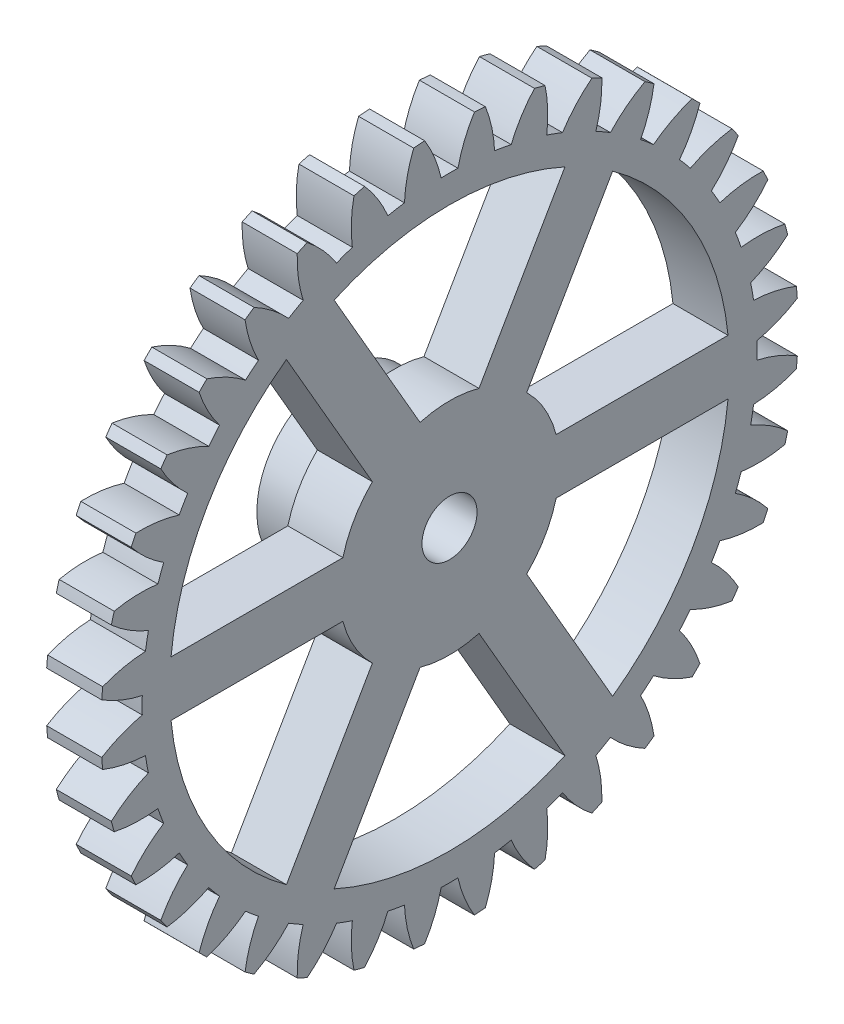
SolidWorks part; units mm, degrees
ref_plane "Plane1" through (0, 0, 0) normal (0, 0, 1) x (1, 0, 0)
ref_plane "Plane2" through (0, 0, 0) normal (0, 1, 0) x (1, 0, 0)
ref_plane "Plane3" through (0, 0, 0) normal (1, 0, 0) x (0, 0, -1)
sketch "HoldingSke" plane through (0, 0, 0) normal (0, 1, 0) x (1, 0, 0)
  line L0 (0, 0) -> (246.5884, -179.1569)
  line L1 (-15, 0) -> (100, 0) construction
  line L2 (0, 0) -> (-2.1039, 2.3779)
  line L3 (0, 0) -> (-11.863, 4.5341)
  line L4 (0, 0) -> (6.9867, 5.0761)
  line L5 (0, 0) -> (-11.8993, -4.4381)
  line L6 (0, 0) -> (-5.2639, -3.5516)
  line L7 (-2.1039, 2.3779) -> (0.6298, 14.7802)
  line L8 (-76.2, 54.61) -> (-69.596, 54.61)
  line L9 (-71.009, 38.7566) -> (-53.1078, 45.2721)
  line L10 (-76.2, 71.12) -> (104.1128, 71.12)
  line L11 (0, 0) -> (-6.35, 0)
  line L12 (-76.2, 101.6) -> (-76.1147, 101.6)
  line L13 (24.9733, 27.94) -> (52.9518, 28.4284)
  line L14 (24.9733, 27.94) -> (24.9746, 27.94)
  line L15 (24.9733, 27.94) -> (100.4006, 29.5858)
  circle A0 centre (0, 0) radius 3.175
  circle A1 centre (0, 0) radius 9.525
  circle A2 centre (0, 0) radius 9.525
  circle A3 centre (0, 0) radius 3.175
  dimension "MHD" = 19.05
  dimension "Hub_dia" = 19.05
  dimension "Bore" = 6.35
  dimension "MBD" = 6.35
  dimension "Num_teeth" = 36
  dimension "Pitch" = 304.8
  dimension "Overall_len" = 12.7
  dimension "Show_teeth" = 36
  dimension "Thickness" = 6.35
  dimension "OAL" = 12.7001
  dimension "T_dim" = 6.604
  dimension "Ap" = 20
  dimension "H" = 19.05
  dimension "Pitch_radius" = 180.3128
  dimension "Width" = 6.35
  dimension "Backlash" = 0.0853
  dimension "Addendum_fac" = 1
  dimension "Dedendum_fac" = 1.25
  dimension "Clearance_fac" = 0.25
  dimension "Dedendum_add" = 0.0013
sketch "BasProSke" plane through (0, 0, 0) normal (0, 1, 0) x (1, 0, 0)
  line L0 (-10, 0) -> (60, 0) construction
  line L1 (0, 0) -> (0, 40.2167)
  line L2 (0, 0) -> (6.35, 0)
  line L3 (6.35, 0) -> (6.35, 40.2167)
  line L4 (6.35, 40.2167) -> (0, 40.2167)
  dimension "Thickness" = 6.35
  dimension "Diameter" = 80.4333
revolve "Base-Revolve" add sketch "BasProSke" angle 360 about L0
sketch "TooCutSke" plane through (0, 0, 0) normal (1, 0, 0) x (0, 0, -1)
  line L1 (0, 0) -> (0, 107) construction
  line L2 (0, 0) -> (-1.8112, 38.0569) construction
  line L3 (0, 0) -> (-6.636, 75.8502) construction
  line L4 (-1.8112, 38.0569) -> (-3.318, 37.9251) construction
  arc A0 (0.9706, 35.4396) -> (-0.9706, 35.4396) centre (0, 0) ccw
  arc A1 (2.8897, 40.1382) -> (-2.8897, 40.1382) centre (0, 0) ccw
  circle A2 centre (0, 0) radius 38.1 construction
  circle A3 centre (0, 0) radius 35.8023 construction
  arc A4 (-0.9706, 35.4396) -> (-2.8897, 40.1382) centre (-15.8417, 32.1068) ccw
  arc A5 (2.8897, 40.1382) -> (0.9706, 35.4396) centre (15.8417, 32.1068) ccw
  dimension "Root_dia" = 70.9058
  dimension "Overcut_dia" = 80.4841
  dimension "Pitch_dia" = 76.2
  dimension "Base_dia" = 71.6046
  dimension "Flank_rad" = 15.24
  dimension "Half_ang" = 5
  dimension "Half_CT" = 1.5125
extrude "ToothCut" cut sketch "TooCutSke" along normal through all
fillet "Breaks" [suppressed] radius 0.0423
fillet "RootFillets" [suppressed] radius 0.5304
pattern_circular "TeethCuts" count 36 every 10 about axis through (-10, 0, 0) along (1, 0, 0) of "ToothCut", "RootFillets", "Breaks"
sketch "HubNeaOneSke" plane through (0, 0, 0) normal (-1, 0, 0) x (0, 0, 1)
  circle A0 centre (0, 0) radius 9.525
  dimension "Diameter" = 19.05
extrude "HubNearOne" add sketch "HubNeaOneSke" along normal blind 6.3501
sketch "HubNeaBotSke" plane through (0, 0, 0) normal (-1, 0, 0) x (0, 0, 1)
  circle A0 centre (0, 0) radius 9.525
  dimension "Diameter" = 19.05
extrude "HubNearBoth" [suppressed] add sketch "HubNeaBotSke" along normal blind 3.175
ref_plane "FarPln" through (6.35, 0, 0) normal (1, 0, 0) x (0, 0, -1)
sketch "HubFarSke" plane through (6.35, 0, 0) normal (1, 0, 0) x (0, 0, -1)
  circle A0 centre (0, 0) radius 9.525
  dimension "Diameter" = 19.05
extrude "HubFar" [suppressed] add sketch "HubFarSke" along normal blind 3.175
sketch "BorSke" plane through (0, 0, 0) normal (1, 0, 0) x (0, 0, -1)
  circle A0 centre (0, 0) radius 3.175
  dimension "Diameter" = 6.35
extrude "Bore" cut sketch "BorSke" along normal mid plane 25.4001
sketch "KeySke" plane through (0, 0, 0) normal (1, 0, 0) x (0, 0, -1)
  line L0 (-0.127, 0) -> (-0.127, 3.429)
  line L1 (-0.127, 3.429) -> (0.127, 3.429)
  line L2 (0.127, 3.429) -> (0.127, 0)
  line L3 (0, 0) -> (0, 34) construction
  line L4 (-0.127, 0) -> (0.127, 0)
  dimension "Offset" = 3.429
  dimension "Width" = 0.254
extrude "Keyway" [suppressed] cut sketch "KeySke" along normal mid plane 25.4001
pattern_circular "Keyway2" [suppressed] count 2 every 90 about axis through (-10, 0, 0) along (1, 0, 0)
sketch "Sketch1" plane through (0, 0, 0) normal (-1, 0, 0) x (0, 0, 1)
  line L0 (-9.525, 0) -> (-35.4529, 0) construction
  line L1 (-4.7625, 8.2489) -> (-17.7264, 30.7031) construction
  line L2 (0, 0) -> (-9.525, 0) construction
  line L3 (0, 0) -> (-4.7625, 8.2489) construction
  line L4 (-8.898, 9.0618) -> (-18.8103, 26.2304)
  line L5 (-12.2967, 3.175) -> (-32.1214, 3.175)
  arc A0 (-35.4396, 0.9706) -> (-35.4396, -0.9706) centre (0, 0) ccw construction
  arc A1 (-35.4529, 0) -> (-17.7264, 30.7031) centre (0, 0) cw construction
  arc A2 (-9.525, 0) -> (-4.7625, 8.2489) centre (0, 0) cw construction
  circle A3 centre (0, 0) radius 9.525 construction
  arc A4 (-32.1214, 3.175) -> (-18.8103, 26.2304) centre (0, 0) cw
  arc A5 (-12.2967, 3.175) -> (-8.898, 9.0618) centre (0, 0) cw
  dimension "D1" = 60
  dimension "D2" = 3.175
extrude "Cut-Extrude1" cut sketch "Sketch1" against normal through all
pattern_circular "CirPattern1" count 6 over 360 about axis through (0, 0, 0) along (1, 0, 0) of "Cut-Extrude1"
equation "' \"Pitch@HoldingSke\" = 4"
equation "' \"Num_teeth@HoldingSke\" = 12"
equation "' \"Ap@HoldingSke\" =  20"
equation "' \"Ap@HoldingSke\" = 20"
equation "' \"Width@HoldingSke\" = 0.5"
equation "' \"Hub_dia@HoldingSke\"= 1"
equation "' \"Hub_dia@HoldingSke\" = 1"
equation "' \"Overall_len@HoldingSke\" = 1.0"
equation "' \"Bore@HoldingSke\" = 0.75"
equation "' \"T_dim@HoldingSke\" = 0.85"
equation "' \"Width@KeySke\" = 0.25"
equation "' \"Show_teeth@HoldingSke\" = 13"
equation "' \"Backlash@HoldingSke\" = 0.009"
equation "' \"Addendum_fac@HoldingSke\" = 1.0"
equation "' \"Dedendum_fac@HoldingSke\" = 1.25"
equation "' \"Dedendum_add@HoldingSke\" = 0.00005"
equation "' \"Clearance_fac@HoldingSke\" = 0.25"
equation "' \"Pitch@HoldingSke\" = 0.5"
equation "' \"Num_teeth@HoldingSke\" = 23"
equation "' \"Show_teeth@HoldingSke\" = 23"
equation "' \"Backlash@HoldingSke\" = 0.0375"
equation "\"Overcut_dia@TooCutSke\" = (\"Num_teeth@HoldingSke\" + 2 * \"Addendum_fac@HoldingSke\") / \"Pitch@HoldingSke\" + 0.002"
equation "\"Pitch_dia@TooCutSke\" = \"Num_teeth@HoldingSke\" / \"Pitch@HoldingSke\""
equation "\"Base_dia@TooCutSke\" = \"Num_teeth@HoldingSke\" / \"Pitch@HoldingSke\" * cos((\"Ap@HoldingSke\"  * 3.14159265 / 180))"
equation "\"Root_dia@TooCutSke\" = (\"Num_teeth@HoldingSke\" + 2) / \"Pitch@HoldingSke\" - 2 * (\"Addendum_fac@HoldingSke\" + \"Dedendum_fac@HoldingSke\") / \"Pitch@HoldingSke\" - \"Dedendum_add@HoldingSke\" * 2"
equation "\"Half_ang@TooCutSke\" = 180 / \"Num_teeth@HoldingSke\""
equation "\"Half_CT@TooCutSke\" = \"Num_teeth@HoldingSke\" / \"Pitch@HoldingSke\" * sin((3.14159265 / 2 / \"Num_teeth@HoldingSke\")) / 2 - 7 * \"Backlash@HoldingSke\" / 4"
equation "\"Flank_rad@TooCutSke\" = \"Num_teeth@HoldingSke\" / \"Pitch@HoldingSke\" / 5"
equation "\"Radius@RootFillets\" = \"Clearance_fac@HoldingSke\" / \"Pitch@HoldingSke\" + \"Dedendum_add@HoldingSke\""
equation "\"Break_rad@Breaks\" = 0.02 / \"Pitch@HoldingSke\""
equation "\"Thickness@HoldingSke\" = \"Width@HoldingSke\""
equation "\"OAL@HoldingSke\" = \"Thickness@HoldingSke\""
equation "\"MHD@HoldingSke\" = (\"Num_teeth@HoldingSke\" + 2) / \"Pitch@HoldingSke\" - 2 * (\"Addendum_fac@HoldingSke\" + \"Dedendum_fac@HoldingSke\")  / \"Pitch@HoldingSke\" - \"Dedendum_add@HoldingSke\" * 2"
equation "\"MBD@HoldingSke\" = (\"Num_teeth@HoldingSke\" + 2) / \"Pitch@HoldingSke\" - 2 * (\"Addendum_fac@HoldingSke\" + \"Dedendum_fac@HoldingSke\")  / \"Pitch@HoldingSke\" - \"Dedendum_add@HoldingSke\" * 2 - 0.002"
equation "\"MHD@HoldingSke\" = ((sgn( \"MHD@HoldingSke\" - \"Hub_dia@HoldingSke\" )-1)*( \"MHD@HoldingSke\" - \"Hub_dia@HoldingSke\" ))/-2+ \"Hub_dia@HoldingSke\""
equation "\"MBD@HoldingSke\" = ((sgn( \"MBD@HoldingSke\" - \"Bore@HoldingSke\" )-1)*( \"MBD@HoldingSke\" - \"Bore@HoldingSke\" ))/-2+ \"Bore@HoldingSke\""
equation "\"OAL@HoldingSke\" = ((sgn( \"OAL@HoldingSke\" - \"Overall_len@HoldingSke\" )+1)*( \"OAL@HoldingSke\" - \"Overall_len@HoldingSke\" ))/2 + \"Overall_len@HoldingSke\" + 0.000002"
equation "\"Num_teeth@TeethCuts\" = int( \"Show_teeth@HoldingSke\" ) + 1"
equation "\"Num_teeth@TeethCuts\" = ((sgn( \"Num_teeth@TeethCuts\" - \"Num_teeth@HoldingSke\" )-1)*( \"Num_teeth@TeethCuts\" - \"Num_teeth@HoldingSke\" ))/-2+ \"Num_teeth@HoldingSke\""
equation "\"Num_teeth@TeethCuts\" = ((sgn( \"Num_teeth@TeethCuts\" - 2.0)+1)*( \"Num_teeth@TeethCuts\" - 2.0))/2 +2.0"
equation "\"Angle@TeethCuts\" = 360.0 / \"Num_teeth@HoldingSke\""
equation "\"Diameter@BasProSke\" = (\"Num_teeth@HoldingSke\" + 2 * \"Addendum_fac@HoldingSke\") / \"Pitch@HoldingSke\""
equation "\"Thickness@BasProSke\"  = \"Thickness@HoldingSke\""
equation "' \"Fillet_rad@BasProSke\" =  \"Thickness@HoldingSke\" * 0.05"
equation "' \"Fillet_rad@BasProSke\" = \"Thickness@HoldingSke\" * 0.05"
equation "\"MHD@HoldingSke\" = ((sgn( \"MHD@HoldingSke\" - \"Root_dia@TooCutSke\" )-1)*( \"MHD@HoldingSke\" - \"Root_dia@TooCutSke\" ))/-2+ \"Root_dia@TooCutSke\""
equation "\"Diameter@HubNeaOneSke\" = \"MHD@HoldingSke\""
equation "\"Length@HubNearOne\" = \"OAL@HoldingSke\" - \"Thickness@BasProSke\""
equation "\"Diameter@HubNeaBotSke\" = \"MHD@HoldingSke\""
equation "\"Length@HubNearBoth\" = ( \"OAL@HoldingSke\" - \"Thickness@BasProSke\" ) / 2.0"
equation "\"Thickness@FarPln\" = \"Thickness@BasProSke\""
equation "\"Diameter@HubFarSke\" = \"MHD@HoldingSke\""
equation "\"Length@HubFar\" = ( \"OAL@HoldingSke\" - \"Thickness@BasProSke\" ) / 2.0"
equation "\"Diameter@BorSke\" = \"MBD@HoldingSke\""
equation "\"D1@Bore\" = \"OAL@HoldingSke\" * 2.0"
equation "\"D1@Keyway\" = \"OAL@HoldingSke\" * 2.0"
equation "\"Offset@KeySke\" = \"T_dim@HoldingSke\" - \"MBD@HoldingSke\" / 2.0"
